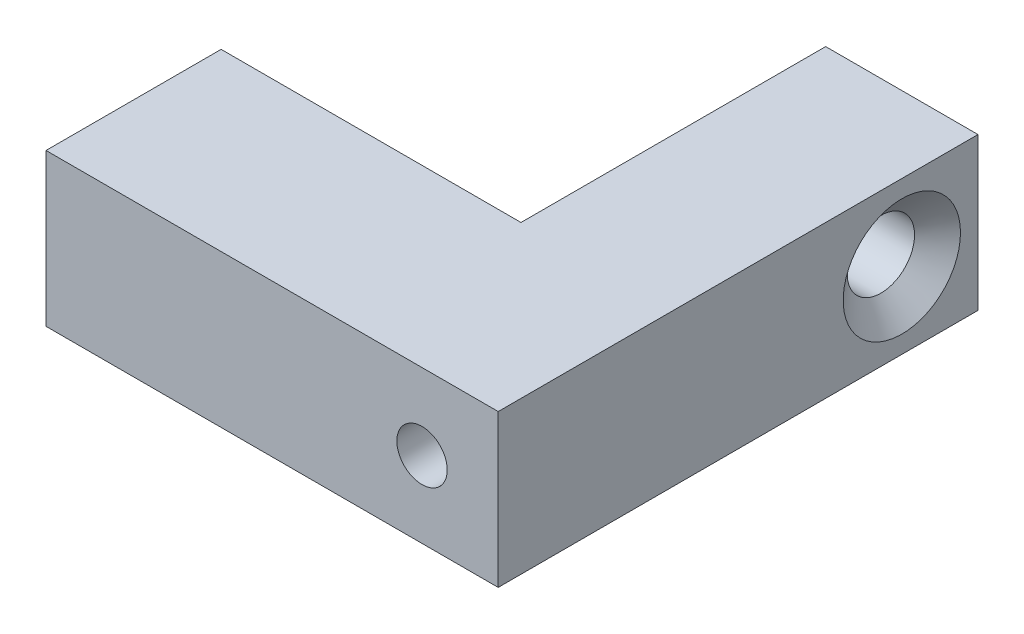
SolidWorks part; units mm, degrees
ref_plane "Front Plane" through (0, 0, 0) normal (0, 0, 1) x (1, 0, 0)
ref_plane "Top Plane" through (0, 0, 0) normal (0, 1, 0) x (1, 0, 0)
ref_plane "Right Plane" through (0, 0, 0) normal (1, 0, 0) x (0, 0, -1)
sketch "Sketch1" plane through (0, 0, 0) normal (0, 1, 0) x (1, 0, 0)
  line L1 (-11.3776, 11.3265) -> (1.3224, 11.3265)
  line L2 (-11.3776, 11.3265) -> (-11.3776, -28.6735)
  line L3 (-11.3776, -28.6735) -> (1.3224, -28.6735)
  line L4 (1.3224, 11.3265) -> (1.3224, -28.6735)
  dimension "D1" = 40
  dimension "D2" = 12.7
extrude "Boss-Extrude1" add sketch "Sketch1" along normal blind 12.7
sketch "Sketch2" plane through (1.3224, 0, 0) normal (1, 0, 0) x (0, 0, -1)
  line L0 (-28.6735, 0) -> (11.3265, 0) construction
  line L1 (11.3265, 12.7) -> (11.3265, 0) construction
  circle A0 centre (4.9765, 6.35) radius 1.9491
  dimension "D1" = 6.35
  dimension "D2" = 6.35
hole_wizard "CSK for #10 Flat Head Machine Screw (100)1" positions "Sketch3" profile "Sketch4" countersink size "#10" standard "ANSI Inch"
sketch "Sketch3" plane through (1.3224, 0, 0) normal (1, 0, 0) x (0, 0, -1)
  point P0 (4.9765, 6.35)
sketch "Sketch4" plane through (1.3224, 6.35, -4.9765) normal (0, 1, 0) x (0, 0, -1)
  line L0 (0, 0) -> (0, 14.3864)
  line L1 (0, 14.3864) -> (2.8067, 12.7)
  line L2 (2.8067, 12.7) -> (2.8067, 1.7477)
  line L3 (2.8067, 1.7477) -> (4.8895, 0)
  line L5 (4.8895, 0) -> (0, 0)
  line L6 (-2.8067, 1.7477) -> (-4.8895, 0) construction
  line L10 (0, 14.3864) -> (-2.8067, 12.7) construction
  line L11 (0, -6.35) -> (0, 107.95) construction
  dimension "Hole Dia." = 5.6134
  dimension "Hole Depth" = 12.7
  dimension "Near C'Sink Dia." = 9.779
  dimension "Near C'Sink Angle" = 100
  dimension "Drill Angle" = 118
sketch "Sketch5" plane through (0, 0, 28.6735) normal (0, 0, 1) x (1, 0, 0)
  line L0 (1.3224, 12.7) -> (1.3224, 0) construction
  line L1 (-11.3776, 0) -> (1.3224, 0) construction
  circle A0 centre (-5.0276, 6.35) radius 1.6485
  dimension "D1" = 6.35
  dimension "D2" = 6.35
hole_wizard "Tap Drill for M5x0.8 Tap1" positions "Sketch6" profile "Sketch7" hole size "M5x0.8" standard "ANSI Metric"
sketch "Sketch6" plane through (0, 0, 28.6735) normal (0, 0, 1) x (1, 0, 0)
  point P0 (-5.0276, 6.35)
sketch "Sketch7" plane through (-5.0276, 6.35, 28.6735) normal (1, 0, 0) x (0, -1, 0)
  line L0 (0, 0) -> (0, 13.9618)
  line L1 (0, 13.9618) -> (2.1, 12.7)
  line L2 (2.1, 12.7) -> (2.1, 0)
  line L5 (2.1, 0) -> (0, 0)
  line L10 (0, 13.9618) -> (-2.1, 12.7) construction
  line L11 (0, -6.35) -> (0, 107.95) construction
  dimension "Hole Dia." = 4.2
  dimension "Hole Depth" = 12.7
  dimension "Drill Angle" = 118
sketch "Sketch8" plane through (-11.3776, 0, 0) normal (-1, 0, 0) x (0, 0, 1)
  line L0 (-11.3265, 12.7) -> (28.6735, 12.7) construction
  line L1 (28.6735, 0) -> (14.0735, 0)
  line L2 (28.6735, 0) -> (28.6735, 12.7)
  line L3 (28.6735, 12.7) -> (14.0735, 12.7)
  line L4 (14.0735, 0) -> (14.0735, 12.7)
  line L5 (-11.3265, 12.7) -> (-11.3265, 0) construction
  dimension "D1" = 25.4
extrude "Boss-Extrude2" add sketch "Sketch8" along normal blind 25
equation "\"D1@Sketch8\"=38.1/2 + 6.35"
